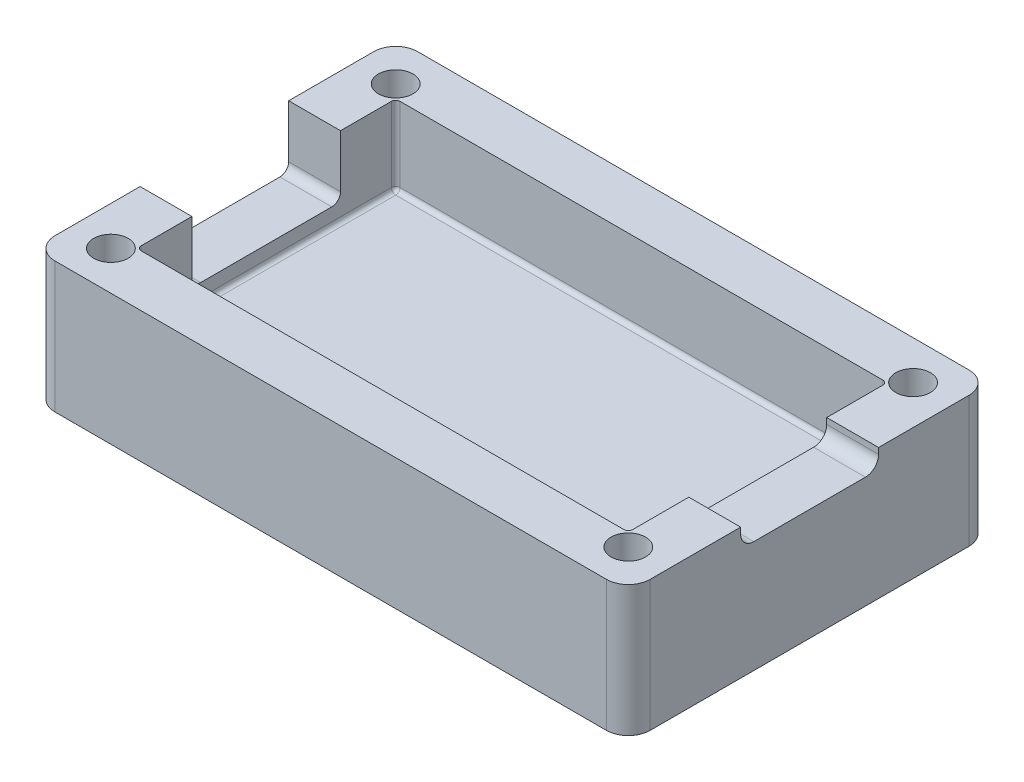
SolidWorks part; units mm, degrees
ref_plane "Front Plane" through (0, 0, 0) normal (0, 0, 1) x (1, 0, 0)
ref_plane "Top Plane" through (0, 0, 0) normal (0, 1, 0) x (1, 0, 0)
ref_plane "Right Plane" through (0, 0, 0) normal (1, 0, 0) x (0, 0, -1)
sketch "Sketch1" plane through (0, 0, 0) normal (0, 1, 0) x (1, 0, 0)
  line L0 (59.9293, 4.4568) -> (59.9293, -13.9892) construction
  line L1 (59.9293, 5.7268) -> (25.4813, 5.7268)
  line L2 (59.9293, 5.7268) -> (59.9293, -15.2592)
  line L3 (59.9293, -15.2592) -> (25.4813, -15.2592)
  line L4 (25.4813, 5.7268) -> (25.4813, -15.2592)
  line L5 (59.9293, 5.7268) -> (25.4813, -15.2592) construction
  line L6 (59.9293, -15.2592) -> (25.4813, 5.7268) construction
  line L7 (26.7513, 5.7268) -> (58.6593, 5.7268) construction
  line L8 (25.4813, -13.9892) -> (25.4813, 4.4568) construction
  line L9 (58.6593, -15.2592) -> (26.7513, -15.2592) construction
  point P0 (0, 0)
extrude "Boss-Extrude1" add sketch "Sketch1" along normal blind 7.572
sketch "Sketch3" plane through (0, 7.572, 0) normal (0, 1, 0) x (1, 0, 0)
  line L1 (56.9293, -12.2592) -> (28.4813, -12.2592)
  line L2 (56.9293, -12.2592) -> (56.9293, 2.7268)
  line L3 (56.9293, 2.7268) -> (28.4813, 2.7268)
  line L4 (28.4813, -12.2592) -> (28.4813, 2.7268)
  line L5 (56.9293, -12.2592) -> (28.4813, 2.7268) construction
  line L6 (56.9293, 2.7268) -> (28.4813, -12.2592) construction
  line L8 (56.9293, 2.4728) -> (56.9293, -0.7748) construction
  line L9 (28.7353, 2.7268) -> (56.6753, 2.7268) construction
  line L10 (56.6753, -12.2592) -> (28.7353, -12.2592) construction
  line L11 (28.4813, -12.0052) -> (28.4813, -9.0657) construction
  point P0 (0, 0)
extrude "Cut-Extrude1" cut sketch "Sketch3" against normal blind 4.572
sketch "Sketch4" plane through (0, 7.572, 0) normal (0, 1, 0) x (1, 0, 0)
  circle A0 centre (57.6774, 3.4749) radius 1
  circle A1 centre (57.6774, -13.0073) radius 1
  circle A2 centre (27.7332, -13.0073) radius 1
  circle A3 centre (27.7332, 3.4749) radius 1
  circle A4 centre (57.6774, 3.4749) radius 1 construction
  circle A5 centre (57.6774, -13.0073) radius 1 construction
  circle A6 centre (27.7332, -13.0073) radius 1 construction
  circle A8 centre (27.7332, 3.4749) radius 1 construction
extrude "Cut-Extrude2" cut sketch "Sketch4" against normal blind 6.19
fillet "Fillet1" radius 1.27 4 edges at (25.4813, 3.786, -5.7268) (59.9293, 3.786, -5.7268) (25.4813, 3.786, 15.2592) (59.9293, 3.786, 15.2592)
fillet "Fillet2" radius 0.254 4 edges at (56.9293, 5.286, -2.7268) (56.9293, 5.286, 12.2592) (28.4813, 5.286, 12.2592) (28.4813, 5.286, -2.7268)
fillet "Fillet3" radius 0.254 8 edges at (56.8549, 3, 12.1848) (42.7053, 3, 12.2592) (28.5557, 3, 12.1848) (28.4813, 3, 4.7662) (28.5557, 3, -2.6524) (42.7053, 3, -2.7268) (56.8549, 3, -2.6524) (56.9293, 3, 4.7662)
sketch "Sketch5" plane through (25.4813, 0, 0) normal (-1, 0, 0) x (0, 0, 1)
  line L0 (-4.4568, 7.572) -> (13.9892, 7.572) construction
  line L1 (9.0657, 7.572) -> (0.4666, 7.572)
  line L2 (9.0657, 7.572) -> (9.0657, 4.0064)
  line L3 (9.0657, 4.0064) -> (0.4666, 4.0064)
  line L4 (0.4666, 7.572) -> (0.4666, 4.0064)
  line L5 (-4.4568, 0) -> (13.9892, 0) construction
  line L6 (0.4666, 9.5831) -> (0.4666, 7.572) construction
  point P8 (4.7662, 7.572)
  point P9 (4.7662, 0)
extrude "Cut-Extrude3" cut sketch "Sketch5" against normal up to surface (3 mm away) up to face at (28.4813, 5.413, 4.7662)
fillet "Fillet4" radius 0.508 2 edges at (26.9813, 4.0064, 0.4666) (26.9813, 4.0064, 9.0657)
ref_plane "Plane1" through (56.6753, 3, -2.4728) normal (0, 0, -1) x (-1, 0, 0)
sketch "Sketch7" plane through (59.9293, 0, 0) normal (1, 0, 0) x (0, 0, -1)
  line L0 (4.4568, 7.572) -> (-0.7748, 7.572) construction
  line L1 (-0.7748, 7.572) -> (-8.7576, 7.572)
  line L2 (-0.7748, 7.572) -> (-0.7748, 6.4638)
  line L3 (-0.7748, 6.4638) -> (-8.7576, 6.4638)
  line L4 (-8.7576, 7.572) -> (-8.7576, 6.4638)
  line L5 (-13.9892, 0) -> (4.4568, 0) construction
  point P6 (-4.7662, 6.4638)
  point P9 (-4.7662, 0)
extrude "Cut-Extrude4" cut sketch "Sketch7" against normal up to surface (3 mm away) up to face at (56.9293, 5.413, 4.7662)
fillet "Fillet5" radius 0.762 2 edges at (58.4293, 6.4638, 8.7576) (58.4293, 6.4638, 0.7748)
